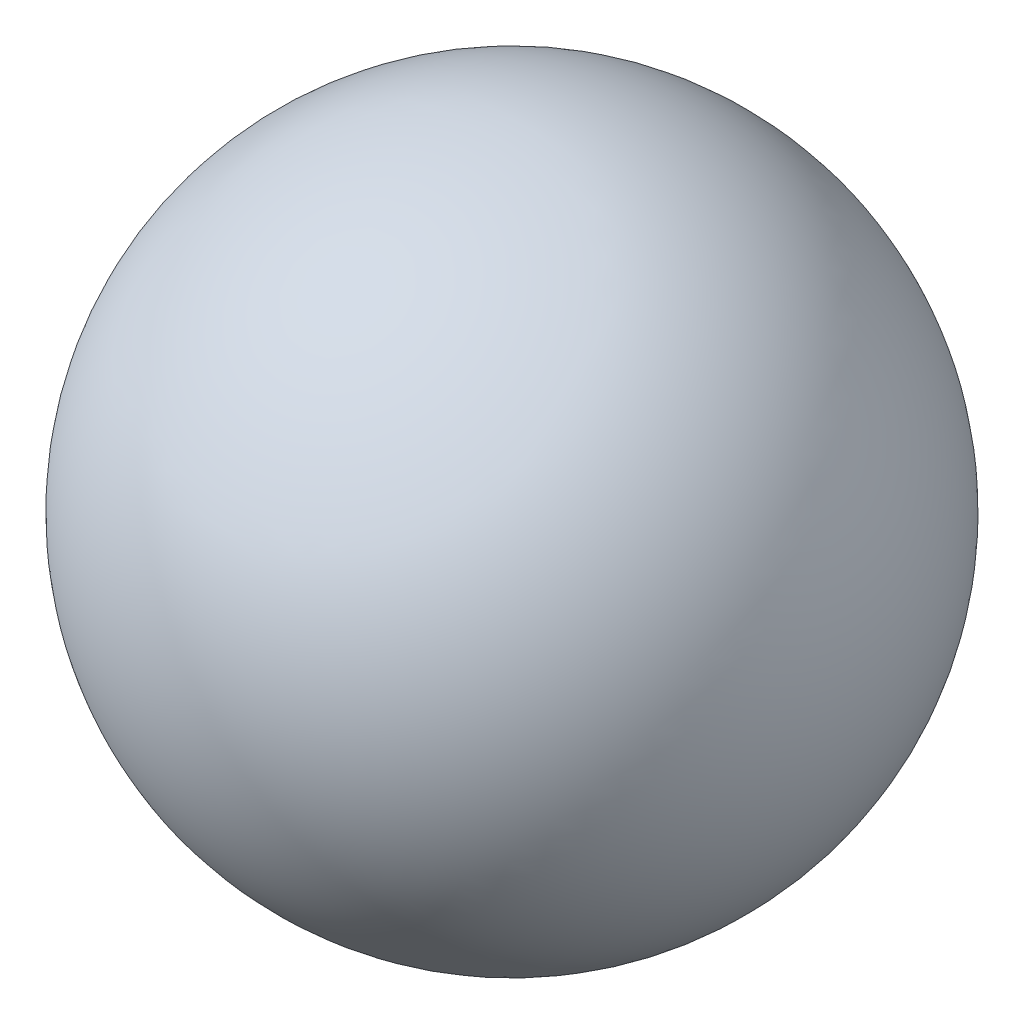
SolidWorks part; units mm, degrees
ref_plane "Front" through (0, 0, 0) normal (0, 0, 1) x (1, 0, 0)
ref_plane "Top" through (0, 0, 0) normal (0, 1, 0) x (1, 0, 0)
ref_plane "Right" through (0, 0, 0) normal (1, 0, 0) x (0, 0, -1)
sketch "Sketch1" plane through (0, 0, 0) normal (0, 1, 0) x (1, 0, 0)
  line L0 (0, 22.6571) -> (0, -22.6571) construction
  line L1 (0, 17.5) -> (0, -17.5)
  arc A0 (0, -17.5) -> (0, 17.5) centre (0, 0) ccw
  dimension "D1" = 17.5
revolve "Revolve1" add sketch "Sketch1" angle 360 about L0
